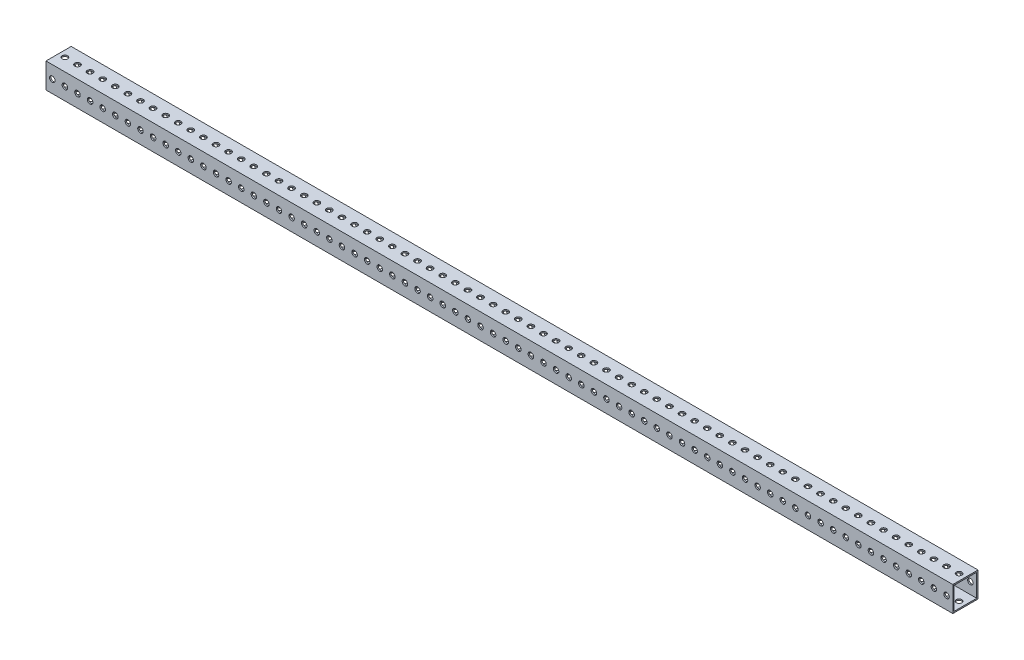
SolidWorks part; units mm, degrees
ref_plane "Front Plane" through (0, 0, 0) normal (0, 0, 1) x (1, 0, 0)
ref_plane "Top Plane" through (0, 0, 0) normal (0, 1, 0) x (1, 0, 0)
ref_plane "Right Plane" through (0, 0, 0) normal (1, 0, 0) x (0, 0, -1)
sketch "Sketch1" plane through (0, 0, 0) normal (1, 0, 0) x (0, 0, -1)
  line L1 (0, 0) -> (-50.8, 0)
  line L2 (0, 0) -> (0, 50.8)
  line L3 (0, 50.8) -> (-50.8, 50.8)
  line L4 (-50.8, 0) -> (-50.8, 50.8)
  dimension "Wd." = 50.8
  dimension "Ht." = 50.8
extrude "Extrude-Thin1" add sketch "Sketch1" along normal mid plane 1828.8 thin
sketch "Sketch2" plane through (0, 0, 0) normal (0, 0, 1) x (1, 0, 0)
  line L0 (-901.7, 25.4) -> (-927.1, 25.4) construction
  line L1 (-914.4, 50.8) -> (-914.4, 0) construction
  line L2 (-901.7, 25.4) -> (-876.3, 25.4) construction
  circle A0 centre (-901.7, 25.4) radius 5.5562
  point P2 (-914.4, 25.4)
  dimension "Hole Dia." = 11.1125
  dimension "Hole Center" = 25.4
extrude "Cut-Extrude1" cut sketch "Sketch2" along normal through all
pattern_linear "LPattern1" count 72 spacing 25.4 along (1, 0, 0) of "Cut-Extrude1"
ref_plane "Plane1" through (0, 0, 0) normal (0, -0.7071, 0.7071) x (1, 0, 0)
mirror "Mirror1" about plane through (0, 0, 0) normal (0, -0.7071, 0.7071) of "LPattern1", "Cut-Extrude1"
equation "\"D3@LPattern1\" = \"Hole Center@Sketch2\""
equation "\"D1@LPattern1\" = \"Length@Extrude-Thin1\" / \"D3@LPattern1\" "
